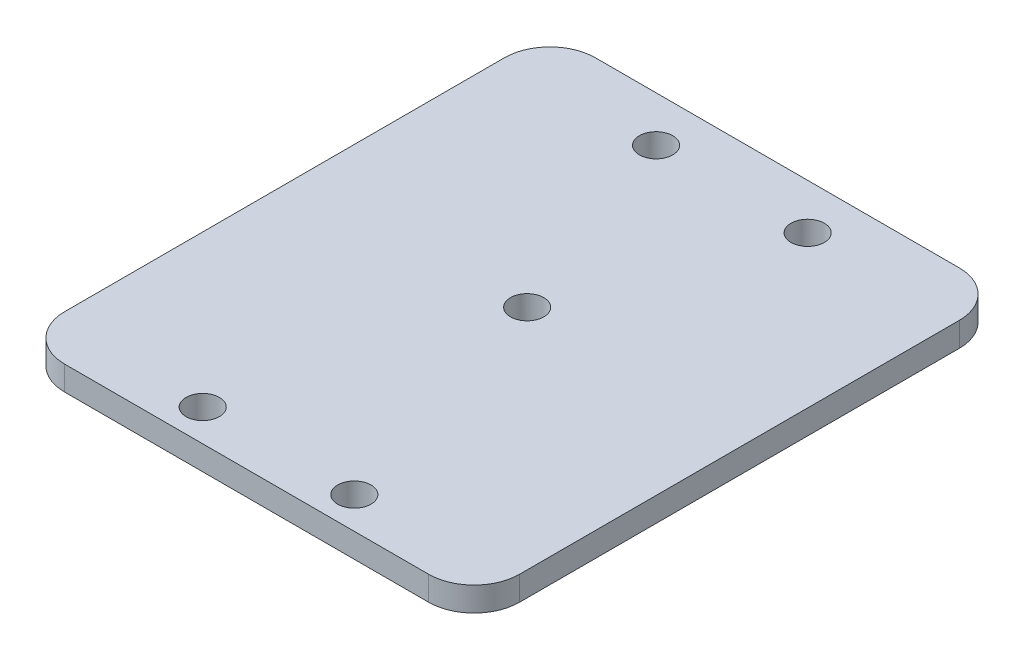
SolidWorks part; units mm, degrees
material "Oshpark board"
ref_plane "Front Plane" through (0, 0, 0) normal (0, 0, 1) x (1, 0, 0)
ref_plane "Top Plane" through (0, 0, 0) normal (0, 1, 0) x (1, 0, 0)
ref_plane "Right Plane" through (0, 0, 0) normal (1, 0, 0) x (0, 0, -1)
sketch "Sketch1" plane through (0, 0, 0) normal (0, 1, 0) x (1, 0, 0)
  line L0 (-15, 17.5) -> (15, -17.5) construction
  line L1 (-15, 17.5) -> (15, 17.5)
  line L2 (-15, 17.5) -> (-15, -17.5)
  line L3 (-15, -17.5) -> (15, -17.5)
  line L4 (15, 17.5) -> (15, -17.5)
  point P4 (0, 0)
  dimension "D1" = 35
  dimension "D2" = 30
extrude "Boss-Extrude1" add sketch "Sketch1" along normal blind 1.6
sketch "Sketch4" plane through (0, 0, 0) normal (0, -1, 0) x (1, 0, 0)
  line L0 (0, -0.88) -> (0, 0.88) construction
  line L1 (-15, 17.5) -> (15, 17.5) construction
  circle A1 centre (0, -9.5) radius 0.75
  dimension "D1" = 1.5
  dimension "D2" = 27
sketch "Sketch5" plane through (0, 0, 0) normal (0, -1, 0) x (1, 0, 0)
  line L2 (15, -17.5) -> (-15, -17.5) construction
  line L3 (-15, 17.5) -> (15, 17.5) construction
  line L12 (7, 17.5) -> (3, 17.5)
  line L13 (7, -17.5) -> (7, 17.5)
  line L14 (3, -17.5) -> (7, -17.5)
  line L15 (3, -7) -> (3, -17.5)
  line L16 (-0.5, -4.5) -> (0.5, -4.5)
  line L17 (-3, -17.5) -> (-3, -7)
  line L18 (-7, -17.5) -> (-3, -17.5)
  line L19 (-7, 17.5) -> (-7, -17.5)
  line L20 (-3, 17.5) -> (-7, 17.5)
  line L21 (-3, 5) -> (-3, 17.5)
  line L22 (0.5, 2.5) -> (-0.5, 2.5)
  line L23 (3, 17.5) -> (3, 5)
  line L24 (7, 17.5) -> (3, 17.5)
  line L25 (7, -17.5) -> (7, 17.5)
  line L26 (3, -17.5) -> (7, -17.5)
  line L27 (3, -7) -> (3, -17.5)
  line L28 (-0.5, -4.5) -> (0.5, -4.5)
  line L29 (-3, -17.5) -> (-3, -7)
  line L30 (-7, -17.5) -> (-3, -17.5)
  line L31 (-7, 17.5) -> (-7, -17.5)
  line L32 (-3, 17.5) -> (-7, 17.5)
  line L33 (-3, 5) -> (-3, 17.5)
  line L34 (0.5, 2.5) -> (-0.5, 2.5)
  line L35 (3, 17.5) -> (3, 5)
  arc A4 (3, -7) -> (0.5, -4.5) centre (0.5, -7) ccw
  arc A5 (-0.5, -4.5) -> (-3, -7) centre (-0.5, -7) ccw
  arc A6 (-3, 5) -> (-0.5, 2.5) centre (-0.5, 5) ccw
  arc A7 (0.5, 2.5) -> (3, 5) centre (0.5, 5) ccw
  arc A8 (3, -7) -> (0.5, -4.5) centre (0.5, -7) ccw
  arc A9 (-0.5, -4.5) -> (-3, -7) centre (-0.5, -7) ccw
  arc A10 (-3, 5) -> (-0.5, 2.5) centre (-0.5, 5) ccw
  arc A11 (0.5, 2.5) -> (3, 5) centre (0.5, 5) ccw
  dimension "D1" = 0
extrude "Cut-Extrude3" cut sketch "Sketch5" against normal blind 0.001
hole_wizard "M2 Clearance Hole1" positions "Sketch2" profile "Sketch3" hole size "M2" standard "ANSI Metric"
sketch "Sketch2" plane through (0, 1.6, 0) normal (0, 1, 0) x (1, 0, 0)
  line L1 (0, 17.5) -> (0, -17.5) construction
  line L2 (15, 17.5) -> (-15, 17.5) construction
  line L3 (-15, -17.5) -> (15, -17.5) construction
  line L5 (-5, 14.5) -> (-5, 17.5) construction
  line L7 (-5, -15.4) -> (-5, -17.5) construction
  line L8 (-15, 17.5) -> (-15, -17.5) construction
  line L9 (0, -2.5) -> (0, 4.5) construction
  line L12 (-0.5, 4.5) -> (0.5, 4.5) construction
  line L13 (0.5, -2.5) -> (-0.5, -2.5) construction
  point P0 (-5, 14.5)
  point P4 (-5, -15.4)
  point P27 (5, -15.4)
  point P29 (5, 14.5)
  point P52 (0, 1)
  dimension "D1" = 10
  dimension "D2" = 32
  dimension "D3" = 20
  dimension "D4" = 2.1
sketch "Sketch3" plane through (-5, 1.6, -14.5) normal (1, 0, 0) x (0, 0, 1)
  line L0 (0, 0) -> (0, 5.8609)
  line L1 (0, 5.8609) -> (1.1, 5.2)
  line L2 (1.1, 5.2) -> (1.1, 0)
  line L5 (1.1, 0) -> (0, 0)
  line L10 (0, 5.8609) -> (-1.1, 5.2) construction
  line L11 (0, -6.35) -> (0, 107.95) construction
  dimension "Hole Dia." = 2.2
  dimension "Hole Depth" = 5.2
  dimension "Drill Angle" = 118
mirror "Mirror1" [suppressed] about plane through (0, 0, 0) normal (1, 0, 0)
sketch "Sketch6" [suppressed] plane through (0, 1.6, 0) normal (0, 1, 0) x (1, 0, 0)
  line L1 (-15, 17.5) -> (-23, 17.5)
  line L2 (-15, 17.5) -> (-15, -17.5)
  line L3 (-15, -17.5) -> (-23, -17.5)
  line L4 (-23, 17.5) -> (-23, -17.5)
  dimension "D1" = 8
extrude "Boss-Extrude2" [suppressed] add sketch "Sketch6" against normal up to surface (1.6 mm away)
mirror "Mirror2" [suppressed] about plane through (0, 0, 0) normal (1, 0, 0)
sketch "Sketch7" [suppressed] plane through (0, 1.6, 0) normal (0, 1, 0) x (1, 0, 0)
  line L1 (-23, 17.5) -> (23, 17.5)
  line L2 (-23, 17.5) -> (-23, 37.5)
  line L3 (-23, 37.5) -> (23, 37.5)
  line L4 (23, 17.5) -> (23, 37.5)
  dimension "D1" = 20
extrude "Boss-Extrude3" [suppressed] add sketch "Sketch7" against normal up to surface (1.6 mm away)
chamfer "Chamfer1" [suppressed] distance 15 angle 30
chamfer "Chamfer2" [suppressed] distance 15 angle 30
fillet "Fillet1" [suppressed] radius 3
sketch "DXFalligners" [suppressed] plane through (0, 1.6, 0) normal (0, 1, 0) x (1, 0, 0)
  line L0 (-23, 21.6962) -> (-23, -14.5) construction
  line L1 (-20, -17.5) -> (20, -17.5) construction
  line L2 (23, 21.6962) -> (23, -14.5) construction
  point P0 (-23, -17.5)
  point P8 (23, -17.5)
fillet "Fillet2" radius 3 4 edges at (15, 0.8, 17.5) (-15, 0.8, 17.5) (-15, 0.8, -17.5) (15, 0.8, -17.5)
